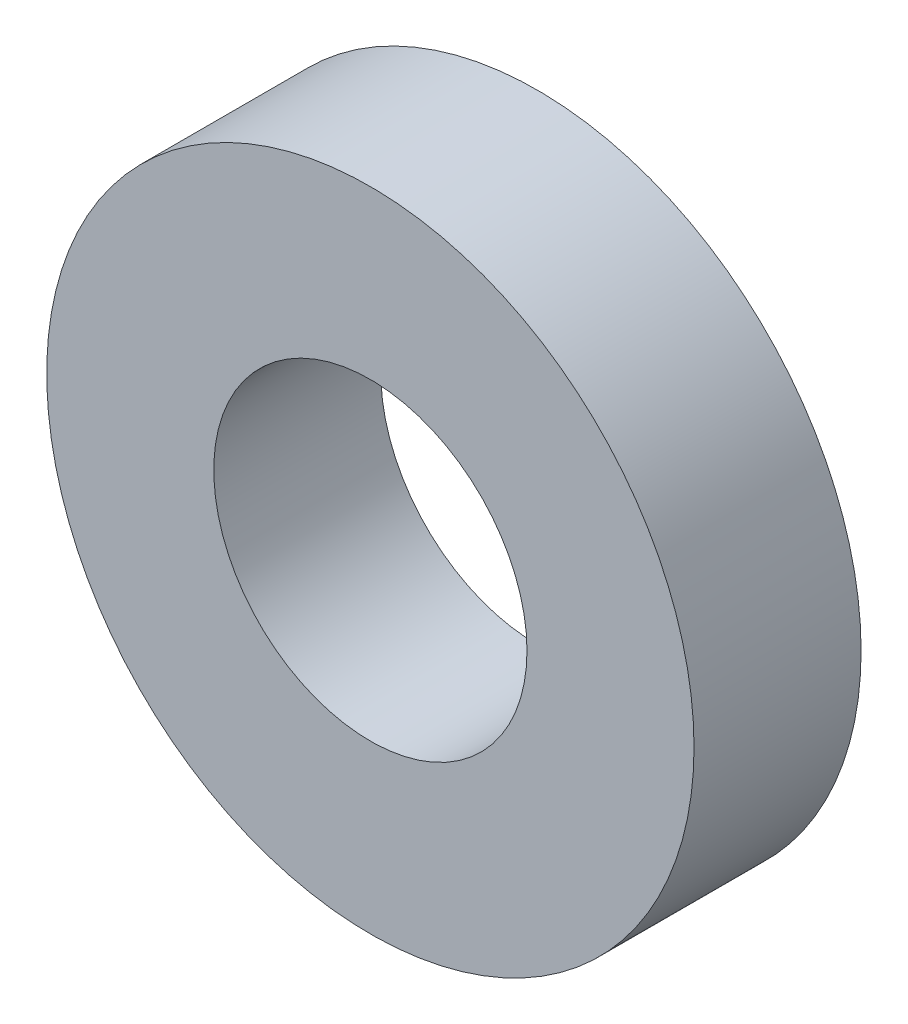
SolidWorks part; units mm, degrees
ref_plane "Plan de face" through (0, 0, 0) normal (0, 0, 1) x (1, 0, 0)
ref_plane "Plan de dessus" through (0, 0, 0) normal (0, 1, 0) x (1, 0, 0)
ref_plane "Plan de droite" through (0, 0, 0) normal (1, 0, 0) x (0, 0, -1)
sketch "Esquisse1" plane through (0, 0, 0) normal (0, 0, 1) x (1, 0, 0)
  circle A0 centre (0, 0) radius 31
  dimension "D1" = 62
extrude "Boss.-Extru.1" add sketch "Esquisse1" along normal blind 16
sketch "Esquisse2" plane through (0, 0, 0) normal (0, 0, 1) x (1, 0, 0)
  circle A0 centre (0, 0) radius 15
  dimension "D1" = 30
extrude "Enlèv. mat.-Extru.1" cut sketch "Esquisse2" along normal through all
